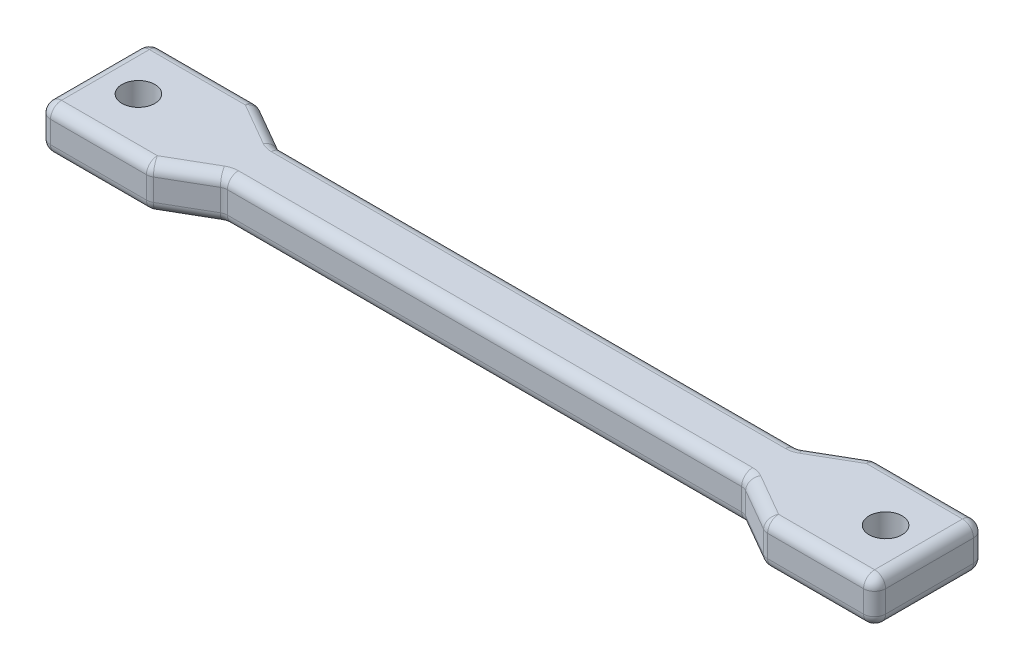
SolidWorks part; units mm, degrees
ref_plane "Front Plane" through (0, 0, 0) normal (0, 0, 1) x (1, 0, 0)
ref_plane "Top Plane" through (0, 0, 0) normal (0, 1, 0) x (1, 0, 0)
ref_plane "Right Plane" through (0, 0, 0) normal (1, 0, 0) x (0, 0, -1)
sketch "Sketch1" plane through (0, 0, 0) normal (0, 1, 0) x (1, 0, 0)
  line L1 (-38, 5) -> (38, 5)
  line L2 (-38, 5) -> (-38, -5)
  line L3 (-38, -5) -> (38, -5)
  line L4 (38, 5) -> (38, -5)
  line L5 (-38, 5) -> (38, -5) construction
  line L6 (-38, -5) -> (38, 5) construction
  point P0 (0, 0)
  dimension "D1" = 76
  dimension "D2" = 10
extrude "Boss-Extrude1" add sketch "Sketch1" along normal blind 4
sketch "Sketch2" plane through (0, 4, 0) normal (0, 1, 0) x (1, 0, 0)
  line L0 (38, -5) -> (38, 5) construction
  line L1 (-38, 5) -> (-38, -5) construction
  circle A0 centre (-34, 0) radius 1.5
  circle A1 centre (34, 0) radius 1.5
  dimension "D3" = 3
  dimension "D4" = 3
  dimension "D1" = 4
  dimension "D2" = 4
extrude "Cut-Extrude1" cut sketch "Sketch2" against normal blind 4
sketch "Sketch3" plane through (0, 4, 0) normal (0, 1, 0) x (1, 0, 0)
  line L0 (-28, 5) -> (-23.6699, 2.5)
  line L1 (38, 5) -> (-38, 5) construction
  line L2 (-23.6699, 2.5) -> (23.6699, 2.5)
  line L3 (23.6699, 2.5) -> (28, 5)
  line L4 (28, 5) -> (-28, 5)
  line L5 (-28, -5) -> (-23.6699, -2.5)
  line L6 (-38, -5) -> (38, -5) construction
  line L7 (-23.6699, -2.5) -> (23.6699, -2.5)
  line L8 (23.6699, -2.5) -> (28, -5)
  line L9 (28, -5) -> (-28, -5)
  dimension "D1" = 10
  dimension "D2" = 10
  dimension "D3" = 10
  dimension "D4" = 10
  dimension "D5" = 5
  dimension "D6" = 2.5
  dimension "D7" = 5
  dimension "D8" = 5
  dimension "D9" = 5
  dimension "D10" = 5
extrude "Cut-Extrude2" cut sketch "Sketch3" against normal blind 10
fillet "Fillet1" radius 1 36 edges at (25.8349, 0, 3.75) (-25.8349, 0, 3.75) (-25.8349, 4, 3.75) (25.8349, 4, 3.75) (-25.8349, 0, -3.75) (25.8349, 0, -3.75) (25.8349, 4, -3.75) (-25.8349, 4, -3.75) (-38, 4, 0) (-38, 0, 0) (-38, 2, 5) (-33, 4, 5) (-28, 2, 5) (-33, 0, 5) (0, 0, 2.5) (-23.6699, 2, 2.5) (0, 4, 2.5) (23.6699, 2, 2.5) (33, 0, 5) (28, 2, 5) (33, 4, 5) (38, 2, 5) (38, 4, 0) (38, 0, 0) (38, 2, -5) (33, 4, -5) (28, 2, -5) (33, 0, -5) (0, 0, -2.5) (23.6699, 2, -2.5) (0, 4, -2.5) (-23.6699, 2, -2.5) (-38, 2, -5) (-33, 0, -5) (-28, 2, -5) (-33, 4, -5)
